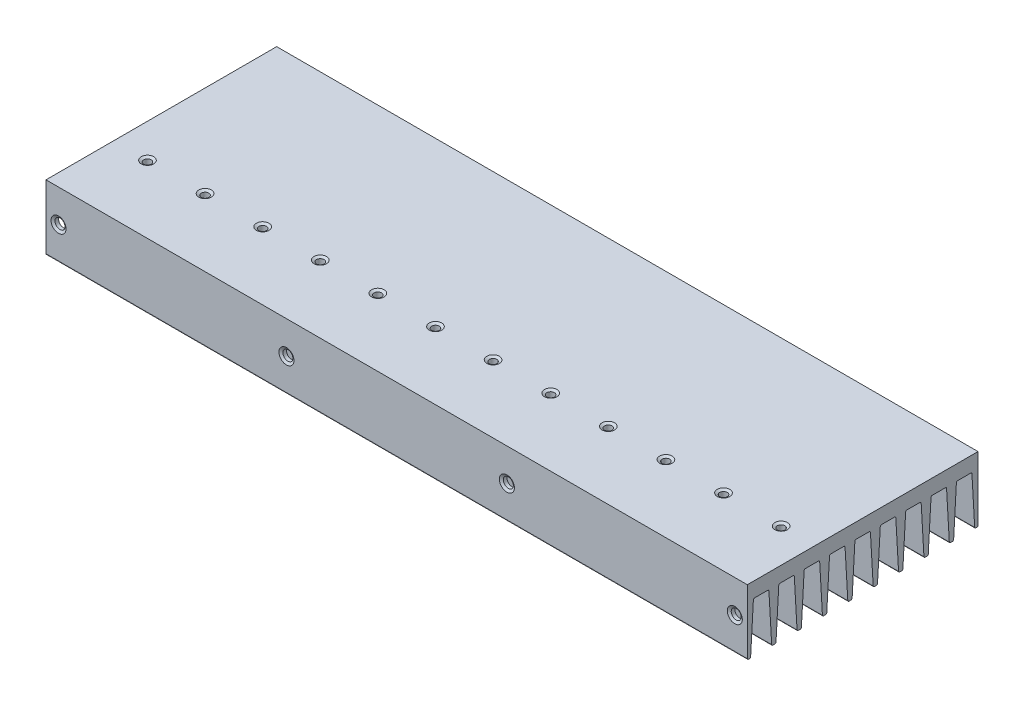
SolidWorks part; units mm, degrees
ref_plane "Front Plane" through (0, 0, 0) normal (0, 0, 1) x (1, 0, 0)
ref_plane "Top Plane" through (0, 0, 0) normal (0, 1, 0) x (1, 0, 0)
ref_plane "Right Plane" through (0, 0, 0) normal (1, 0, 0) x (0, 0, -1)
sketch "Sketch1" plane through (0, 0, 0) normal (1, 0, 0) x (0, 0, -1)
  line L0 (-44.75, -13) -> (-43.6, 7)
  line L1 (-46.05, 13) -> (46.05, 13)
  line L2 (-46.05, 13) -> (-46.05, -13)
  line L3 (-46.05, -13) -> (-44.75, -13)
  line L4 (46.05, 13) -> (46.05, -13)
  line L5 (-46.05, 13) -> (36.4557, -10.2915) construction
  line L6 (-46.05, -13) -> (-44.7285, -12.627) construction
  line L7 (-43.6, 7) -> (-37.45, 7)
  line L8 (-40.525, -11.4403) -> (-40.525, -21.1628) construction
  line L9 (-36.3, -13) -> (-37.45, 7)
  line L10 (-33.4688, 7) -> (-27.3187, 7)
  line L11 (-26.1687, -13) -> (-27.3187, 7)
  line L12 (-34.6188, -13) -> (-33.4688, 7)
  line L13 (-23.3375, 7) -> (-17.1875, 7)
  line L14 (-16.0375, -13) -> (-17.1875, 7)
  line L15 (-24.4875, -13) -> (-23.3375, 7)
  line L16 (-13.2063, 7) -> (-7.0563, 7)
  line L17 (-5.9063, -13) -> (-7.0563, 7)
  line L18 (-14.3563, -13) -> (-13.2063, 7)
  line L19 (-3.075, 7) -> (3.075, 7)
  line L20 (4.225, -13) -> (3.075, 7)
  line L21 (-4.225, -13) -> (-3.075, 7)
  line L22 (7.0562, 7) -> (13.2062, 7)
  line L23 (14.3562, -13) -> (13.2062, 7)
  line L24 (5.9062, -13) -> (7.0562, 7)
  line L25 (17.1875, 7) -> (23.3375, 7)
  line L26 (24.4875, -13) -> (23.3375, 7)
  line L27 (16.0375, -13) -> (17.1875, 7)
  line L28 (27.3187, 7) -> (33.4687, 7)
  line L29 (34.6187, -13) -> (33.4687, 7)
  line L30 (26.1687, -13) -> (27.3187, 7)
  line L31 (37.45, 7) -> (43.6, 7)
  line L32 (44.75, -13) -> (43.6, 7)
  line L33 (36.3, -13) -> (37.45, 7)
  line L34 (0, 0) -> (0, 18.1093) construction
  line L35 (-44.75, -13) -> (-40.525, -13) construction
  line L36 (-36.3, -13) -> (-34.6188, -13)
  line L37 (-44.7285, -12.627) -> (-40.525, -11.4403) construction
  line L38 (-36.4557, -10.2915) -> (46.05, 13) construction
  line L39 (-40.525, 7) -> (-40.525, -11.4403) construction
  line L40 (-40.525, -11.4403) -> (-36.4557, -10.2915) construction
  line L41 (-40.525, -13) -> (-36.3, -13) construction
  line L42 (-34.6188, -13) -> (-26.1687, -13) construction
  line L43 (-26.1687, -13) -> (-24.4875, -13)
  line L44 (-24.4875, -13) -> (-16.0375, -13) construction
  line L45 (-16.0375, -13) -> (-14.3563, -13)
  line L46 (-14.3563, -13) -> (-5.9063, -13) construction
  line L47 (-5.9063, -13) -> (-4.225, -13)
  line L48 (-4.225, -13) -> (4.225, -13) construction
  line L49 (4.225, -13) -> (5.9062, -13)
  line L50 (5.9062, -13) -> (14.3562, -13) construction
  line L51 (14.3562, -13) -> (16.0375, -13)
  line L52 (16.0375, -13) -> (24.4875, -13) construction
  line L53 (24.4875, -13) -> (26.1687, -13)
  line L54 (26.1687, -13) -> (34.6187, -13) construction
  line L55 (34.6187, -13) -> (36.3, -13)
  line L56 (36.3, -13) -> (44.75, -13) construction
  line L57 (44.75, -13) -> (46.05, -13)
  line L58 (36.4557, -10.2915) -> (44.7285, -12.627) construction
  line L59 (44.7285, -12.627) -> (46.05, -13) construction
  point P0 (0, 0)
  dimension "D1" = 92.1
  dimension "D2" = 26
  dimension "D3" = 1.3
  dimension "D4" = 2.45
  dimension "D5" = 20
  dimension "D6" = 8.45
  dimension "D7" = 9
  dimension "D8" = 8.45
  dimension "D9" = 6.582
extrude "Boss-Extrude1" add sketch "Sketch1" along normal mid plane 280
fillet "Fillet1" radius 0.5 38 edges at (0, -13, -46.05) (0, -13, -44.75) (0, 7, -43.6) (0, 7, -37.45) (0, -13, -36.3) (0, -13, -34.6187) (0, 7, -33.4687) (0, -13, -26.1687) (0, 7, -27.3187) (0, 7, -23.3375) (0, -13, -24.4875) (0, 7, -17.1875) (0, 7, -13.2062) (0, -13, -16.0375) (0, -13, -5.9062) (0, -13, -14.3562) (0, 7, -7.0562) (0, -13, -4.225) (0, 7, 3.075) (0, 7, -3.075) (0, -13, 4.225) (0, 7, 7.0563) (0, -13, 5.9063) (0, 7, 13.2063) (0, -13, 14.3563) (0, -13, 16.0375) (0, 7, 17.1875) (0, -13, 24.4875) (0, 7, 23.3375) (0, 7, 27.3187) (0, -13, 26.1687) (0, 7, 33.4688) (0, -13, 34.6188) (0, -13, 36.3) (0, 7, 37.45) (0, 7, 43.6) (0, -13, 44.75) (0, -13, 46.05)
sketch "Sketch2" plane through (0, 13, 0) normal (0, 1, 0) x (1, 0, 0)
  line L0 (140, 46.05) -> (140, -46.05) construction
  circle A0 centre (126.5, -19.05) radius 1.5
  circle A1 centre (103.5, -19.05) radius 1.5
  circle A2 centre (80.5, -19.05) radius 1.5
  circle A3 centre (57.5, -19.05) radius 1.5
  circle A4 centre (34.5, -19.05) radius 1.5
  circle A5 centre (11.5, -19.05) radius 1.5
  circle A6 centre (-11.5, -19.05) radius 1.5
  circle A7 centre (-34.5, -19.05) radius 1.5
  circle A8 centre (-57.5, -19.05) radius 1.5
  circle A9 centre (-80.5, -19.05) radius 1.5
  circle A10 centre (-103.5, -19.05) radius 1.5
  circle A11 centre (-126.5, -19.05) radius 1.5
  arc A12 (101.85, -19.05) -> (105.15, -19.05) centre (103.5, -19.05) ccw construction
  dimension "D1" = 3
  dimension "D2" = 13.5
  dimension "D3" = 12
extrude "Cut-Extrude1" cut sketch "Sketch2" against normal blind 20
chamfer "Chamfer1" distance 1 angle 30 12 edges at (-126.5, 13, 20.55) (-103.5, 13, 20.55) (-80.5, 13, 20.55) (-57.5, 13, 20.55) (-34.5, 13, 20.55) (-11.5, 13, 20.55) (11.5, 13, 20.55) (34.5, 13, 20.55) (57.5, 13, 20.55) (80.5, 13, 20.55) (103.5, 13, 20.55) (126.5, 13, 20.55)
sketch "Sketch3" plane through (0, 0, 46.05) normal (0, 0, 1) x (1, 0, 0)
  line L0 (140, 0) -> (-140, 0) construction
  line L1 (-140, 13) -> (-140, -12.5) construction
  line L2 (0, 0) -> (0, 50.7494) construction
  circle A0 centre (-135, 0) radius 2
  circle A1 centre (-44, 0) radius 2
  circle A2 centre (44, 0) radius 2
  circle A3 centre (135, 0) radius 2
  point P6 (0, 0)
  dimension "D1" = 4
  dimension "D2" = 5
  dimension "D3" = 88
  dimension "D4" = 91
extrude "Cut-Extrude2" cut sketch "Sketch3" against normal blind 5
chamfer "Chamfer2" distance 1 angle 30 4 edges at (133, 0, 46.05) (42, 0, 46.05) (-42, 0, 46.05) (-133, 0, 46.05)
